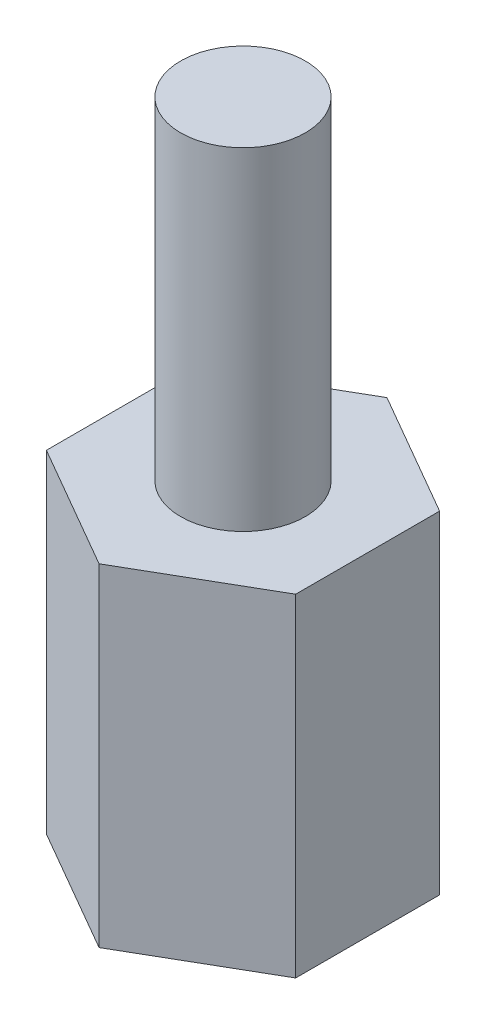
SolidWorks part; units mm, degrees
ref_plane "Front Plane" through (0, 0, 0) normal (0, 0, 1) x (1, 0, 0)
ref_plane "Top Plane" through (0, 0, 0) normal (0, 1, 0) x (1, 0, 0)
ref_plane "Right Plane" through (0, 0, 0) normal (1, 0, 0) x (0, 0, -1)
sketch "Sketch1" plane through (0, 0, 0) normal (0, 1, 0) x (1, 0, 0)
  line L1 (0, 3.4641) -> (-3, 1.7321)
  line L2 (-3, 1.7321) -> (-3, -1.7321)
  line L3 (-3, -1.7321) -> (0, -3.4641)
  line L4 (0, -3.4641) -> (3, -1.7321)
  line L5 (3, -1.7321) -> (3, 1.7321)
  line L6 (3, 1.7321) -> (0, 3.4641)
  circle A0 centre (0, 0) radius 3 construction
  circle A1 centre (0, 0) radius 1.5
  dimension "D1" = 6
  dimension "D2" = 3
extrude "Boss-Extrude1" add sketch "Sketch1" along normal blind 8
sketch "Sketch2" plane through (0, 8, 0) normal (0, 1, 0) x (1, 0, 0)
  circle A0 centre (0, 0) radius 1.5 construction
  circle A1 centre (0, 0) radius 1.5
extrude "Boss-Extrude2" add sketch "Sketch2" along normal blind 11 from offset 3
